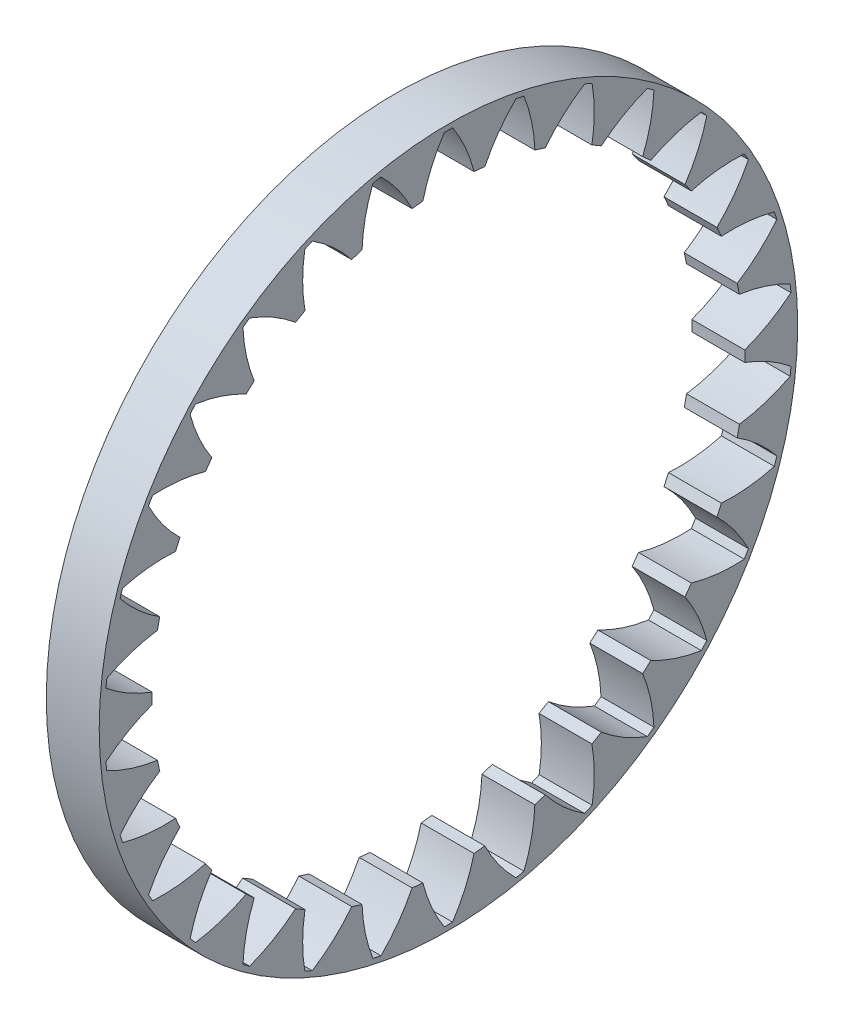
SolidWorks part; units mm, degrees
ref_plane "Plane1" through (0, 0, 0) normal (0, 0, 1) x (1, 0, 0)
ref_plane "Plane2" through (0, 0, 0) normal (0, 1, 0) x (1, 0, 0)
ref_plane "Plane3" through (0, 0, 0) normal (1, 0, 0) x (0, 0, -1)
sketch "HoldingSke" plane through (0, 0, 0) normal (0, 1, 0) x (1, 0, 0)
  line L0 (0, 0) -> (0.433, -0.25)
  line L1 (-15, 0) -> (100, 0) construction
  line L2 (0, 0) -> (-2.1039, 2.3779)
  line L3 (0, 0) -> (-11.863, 4.5341)
  line L4 (0, 0) -> (7.479, 4.318)
  line L5 (0, 0) -> (-23.7986, -8.8762)
  line L6 (0, 0) -> (-10.5278, -7.1032)
  line L7 (-2.1039, 2.3779) -> (3.3635, 27.1825)
  line L8 (-76.2, 4.3779) -> (-54.61, 4.3779)
  line L9 (-71.009, 38.7566) -> (-53.1078, 45.2721)
  line L10 (-76.2, 71.12) -> (104.1128, 71.12)
  line L11 (0, 0) -> (-5, 0)
  line L12 (-76.2, 101.6) -> (-76.133, 101.6)
  line L13 (24.9733, 27.94) -> (52.9518, 28.4284)
  line L14 (24.9733, 27.94) -> (24.9743, 27.94)
  line L15 (24.9733, 27.94) -> (100.4006, 29.5858)
  circle A0 centre (0, 0) radius 35
  circle A1 centre (0, 0) radius 12.7
  circle A2 centre (0, 0) radius 12.7
  dimension "MHD" = 25.4
  dimension "Hub_dia" = 25.4
  dimension "Diameter" = 70
  dimension "Num_teeth" = 30
  dimension "Pitch" = 0.5
  dimension "Overall_len" = 25.4
  dimension "Show_teeth" = 30
  dimension "Thickness" = 12.7
  dimension "OAL" = 25.4001
  dimension "T_dim" = 21.59
  dimension "Ap" = 20
  dimension "H" = 19.05
  dimension "Pitch_radius" = 180.3128
  dimension "Width" = 5
  dimension "Backlash" = 0.067
  dimension "Addendum_fac" = 1
  dimension "Dedendum_fac" = 1.25
  dimension "Clearance_fac" = 0.25
  dimension "Dedendum_add" = 0.001
  dimension "Module" = 2
sketch "BasProSke" plane through (0, 0, 0) normal (0, 1, 0) x (1, 0, 0)
  line L0 (-10, 0) -> (60, 0) construction
  line L1 (0, 28) -> (0, 35)
  line L2 (0, 28) -> (5, 28)
  line L3 (5, 28) -> (5, 35)
  line L4 (5, 35) -> (0, 35)
  dimension "Diameter" = 70
  dimension "Thickness" = 5
  dimension "Inside_diameter" = 56
revolve "Base-Revolve" add sketch "BasProSke" angle 360 about L0
sketch "TooCutSke" plane through (0, 0, 0) normal (1, 0, 0) x (0, 0, -1)
  line L3 (1.7376, 29.9496) -> (1.7376, 53.6633) construction
  line L4 (0, 0) -> (0, 59.563) construction
  line L5 (0, 0) -> (-7.1422, 67.9532) construction
  line L6 (-12.1318, 24.2364) -> (34.9834, 29.1884) construction
  circle A0 centre (0, 0) radius 30 construction
  circle A1 centre (0, 0) radius 32.501 construction
  circle A2 centre (0, 0) radius 25.3717 construction
  circle A3 centre (0, 0) radius 27.9746 construction
  arc A4 (2.4216, 27.8696) -> (0.3876, 32.4987) centre (-12.1318, 24.2364) ccw
  arc A5 (2.4216, 27.8696) -> (-2.4216, 27.8696) centre (0, 0) ccw
  arc A6 (0.3876, 32.4987) -> (-0.3876, 32.4987) centre (0, 0) ccw
  arc A7 (-0.3876, 32.4987) -> (-2.4216, 27.8696) centre (12.1318, 24.2364) ccw
  dimension "Pitch_dia" = 60
  dimension "Base_dia" = 50.7434
  dimension "Root_dia" = 65.002
  dimension "Overcut_dia" = 55.9492
  dimension "Flank_rad" = 15
  dimension "Half_ang" = 6
  dimension "Half_CT" = 1.7376
extrude "ToothCut" cut sketch "TooCutSke" along normal through all
fillet "Breaks" [suppressed] radius 0.2
fillet "RootFillets" [suppressed] radius 0.501
pattern_circular "TeethCuts" count 30 every 12 about axis through (-10, 0, 0) along (1, 0, 0) of "RootFillets", "Breaks", "ToothCut"
sketch "Croquis1" plane through (5, 0, 0) normal (1, 0, 0) x (0, 0, -1)
  circle A0 centre (0, 0) radius 33
  dimension "D1" = 66
extrude "Cortar-Extruir1" cut sketch "Croquis1" against normal through all flip side to cut
equation "' \"Module@HoldingSke\" = 6.35"
equation "' \"Num_teeth@HoldingSke\" = 24"
equation "' \"Ap@HoldingSke\" =  14.5"
equation "' \"Ap@HoldingSke\" = 14.5"
equation "' \"Width@HoldingSke\" = 12"
equation "' \"Diameter@HoldingSke\" = 8 * 25.4"
equation "' \"Show_teeth@HoldingSke\" = 100"
equation "' \"Backlash@HoldingSke\" = 0.009 * 25.4"
equation "' \"Addendum_fac@HoldingSke\" = 1.0"
equation "' \"Dedendum_fac@HoldingSke\" = 1.25"
equation "' \"Dedendum_add@HoldingSke\" = 0.00005 * 25.4"
equation "' \"Clearance_fac@HoldingSke\" = 0.25"
equation "\"Pitch@HoldingSke\" = 1 / \"Module@HoldingSke\" "
equation "\"Overcut_dia@TooCutSke\" = (\"Num_teeth@HoldingSke\" - 2 * \"Addendum_fac@HoldingSke\") / \"Pitch@HoldingSke\" - 0.002 * 25.4"
equation "\"Pitch_dia@TooCutSke\" = \"Num_teeth@HoldingSke\" / \"Pitch@HoldingSke\""
equation "\"Base_dia@TooCutSke\" = \"Num_teeth@HoldingSke\" / \"Pitch@HoldingSke\" * cos((\"Ap@HoldingSke\"  * 3.14159265 / 180)) * 0.90"
equation "\"Root_dia@TooCutSke\" = \"Num_teeth@HoldingSke\"  / \"Pitch@HoldingSke\" + 2 *  \"Dedendum_fac@HoldingSke\"/ \"Pitch@HoldingSke\" + \"Dedendum_add@HoldingSke\" * 2"
equation "\"Half_ang@TooCutSke\" = 180 / \"Num_teeth@HoldingSke\""
equation "\"Half_CT@TooCutSke\" = \"Num_teeth@HoldingSke\" / \"Pitch@HoldingSke\" * sin((3.14159265 / 2 / \"Num_teeth@HoldingSke\")) / 2 + 10 * \"Backlash@HoldingSke\" / 4"
equation "\"Flank_rad@TooCutSke\" = \"Num_teeth@HoldingSke\" / \"Pitch@HoldingSke\" / 4"
equation "\"Radius@RootFillets\"= \"Clearance_fac@HoldingSke\" / \"Pitch@HoldingSke\" + \"Dedendum_add@HoldingSke\""
equation "\"Break_rad@Breaks\" = 0.02 / \"Pitch@HoldingSke\" * 5"
equation "\"Num_teeth@TeethCuts\" = int( \"Show_teeth@HoldingSke\" ) + 1"
equation "\"Num_teeth@TeethCuts\" = ((sgn( \"Num_teeth@TeethCuts\" - \"Num_teeth@HoldingSke\" )-1)*( \"Num_teeth@TeethCuts\" - \"Num_teeth@HoldingSke\" ))/-2+ \"Num_teeth@HoldingSke\""
equation "\"Num_teeth@TeethCuts\" = ((sgn( \"Num_teeth@TeethCuts\" - 2.0)+1)*( \"Num_teeth@TeethCuts\" - 2.0))/2 +2.0"
equation "\"Angle@TeethCuts\" = 360.0 / \"Num_teeth@HoldingSke\""
equation "\"Diameter@BasProSke\" = \"Num_teeth@HoldingSke\"  / \"Pitch@HoldingSke\" + 2 *  \"Dedendum_fac@HoldingSke\"/ \"Pitch@HoldingSke\" + \"Dedendum_add@HoldingSke\" * 2 + 0.002 * 25.4"
equation "\"Diameter@BasProSke\" = ((sgn( \"Diameter@BasProSke\"  - \"Diameter@HoldingSke\" )+1)*( \"Diameter@BasProSke\"  - \"Diameter@HoldingSke\" ))/2 + \"Diameter@HoldingSke\""
equation "\"Inside_diameter@BasProSke\" =  (\"Num_teeth@HoldingSke\" - 2 * \"Addendum_fac@HoldingSke\") / \"Pitch@HoldingSke\" "
equation "\"Thickness@BasProSke\"  = \"Width@HoldingSke\""
